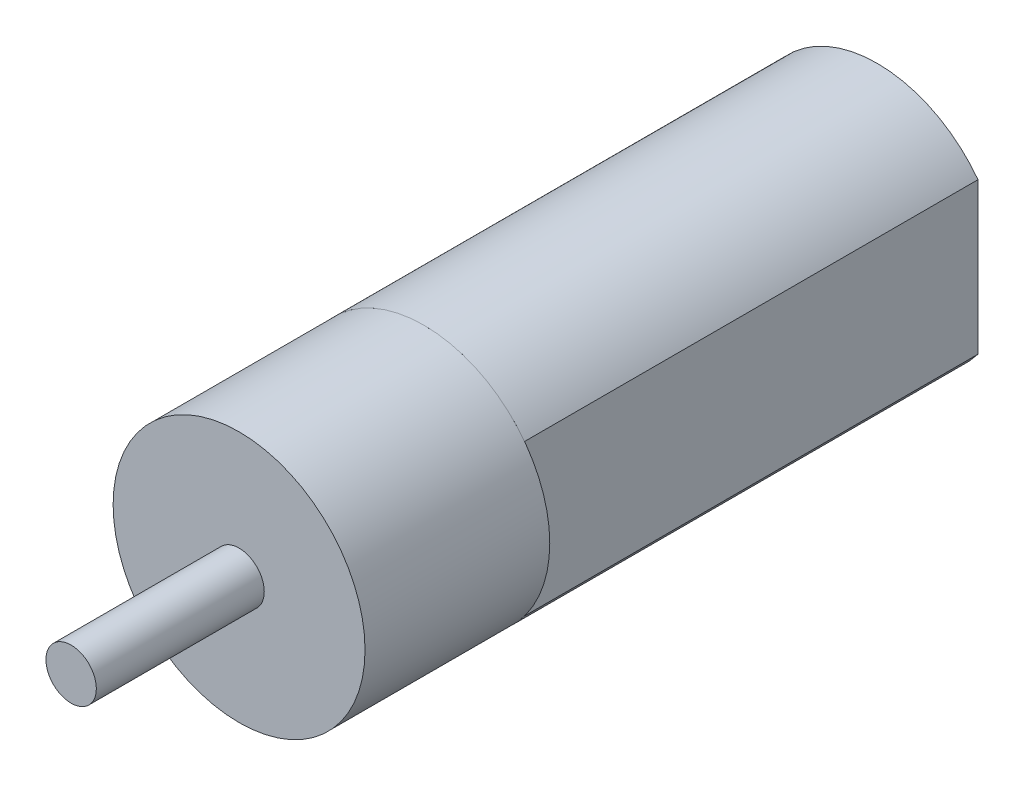
SolidWorks part; units mm, degrees
ref_plane "Alzado" through (0, 0, 0) normal (0, 0, 1) x (1, 0, 0)
ref_plane "Planta" through (0, 0, 0) normal (0, 1, 0) x (1, 0, 0)
ref_plane "Vista lateral" through (0, 0, 0) normal (1, 0, 0) x (0, 0, -1)
sketch "Croquis1" plane through (0, 0, 0) normal (0, 0, 1) x (1, 0, 0)
  circle A0 centre (0, 0) radius 7.5
  dimension "D1" = 15
extrude "Saliente-Extruir1" add sketch "Croquis1" along normal blind 11
sketch "Croquis2" plane through (0, 0, 11) normal (0, 0, 1) x (1, 0, 0)
  circle A0 centre (0, 0) radius 1.5
  dimension "D1" = 3
extrude "Saliente-Extruir2" add sketch "Croquis2" along normal blind 10
sketch "Croquis3" plane through (0, 0, 0) normal (0, 0, -1) x (-1, 0, 0)
  line L2 (-6, 4.5) -> (-6, -4.5)
  line L4 (6, 4.5) -> (6, -4.5)
  line L5 (-6, 4.5) -> (6, -4.5) construction
  line L6 (-6, -4.5) -> (6, 4.5) construction
  arc A0 (-6, -4.5) -> (6, -4.5) centre (0, 0) ccw
  circle A1 centre (0, 0) radius 7.5 construction
  arc A2 (6, 4.5) -> (-6, 4.5) centre (0, 0) ccw
  point P7 (-3.2379, -6.7651)
  dimension "D1" = 12
extrude "Saliente-Extruir3" add sketch "Croquis3" along normal blind 27 separate body
